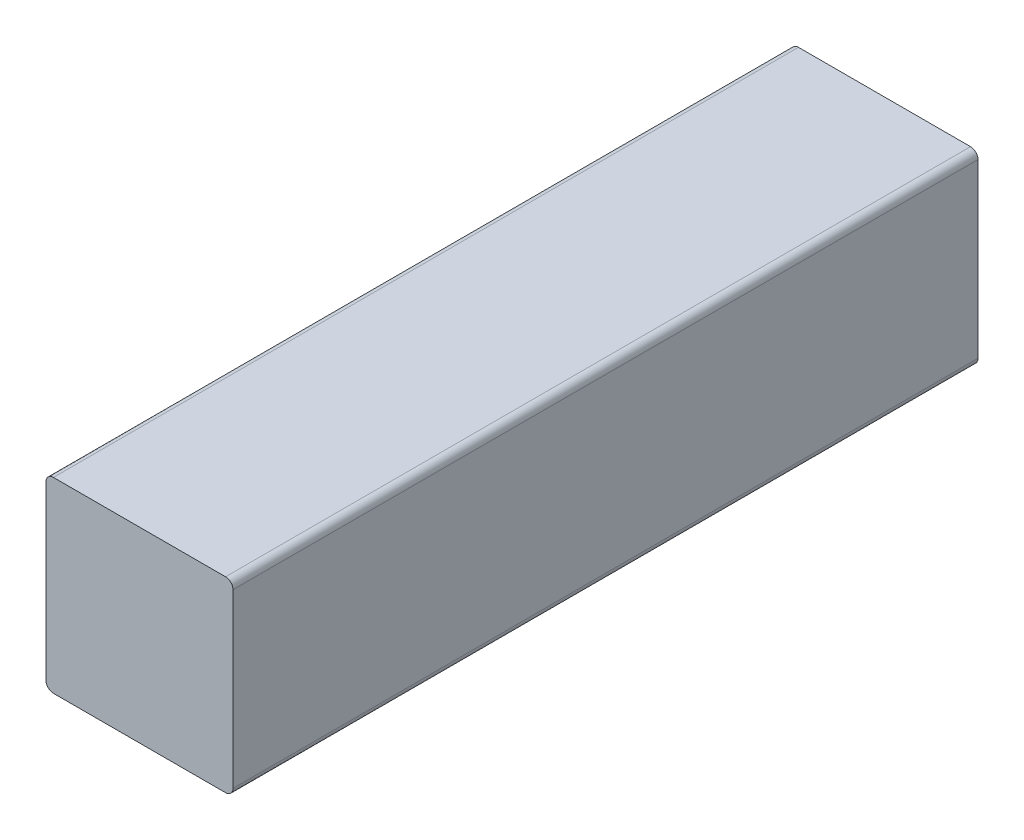
SolidWorks part; units mm, degrees
ref_plane "Front Plane" through (0, 0, 0) normal (0, 0, 1) x (1, 0, 0)
ref_plane "Top Plane" through (0, 0, 0) normal (0, 1, 0) x (1, 0, 0)
ref_plane "Right Plane" through (0, 0, 0) normal (1, 0, 0) x (0, 0, -1)
sketch "Sketch1" plane through (0, 0, 0) normal (0, 0, 1) x (1, 0, 0)
  line L0 (0.254, 0) -> (6.1214, 0)
  line L1 (6.3754, 0.254) -> (6.3754, 6.1214)
  line L2 (6.1214, 6.3754) -> (0.254, 6.3754)
  line L3 (0, 6.1214) -> (0, 0.254)
  arc A0 (0.254, 6.3754) -> (0, 6.1214) centre (0.254, 6.1214) ccw
  arc A1 (6.3754, 6.1214) -> (6.1214, 6.3754) centre (6.1214, 6.1214) ccw
  arc A2 (6.1214, 0) -> (6.3754, 0.254) centre (6.1214, 0.254) ccw
  arc A3 (0, 0.254) -> (0.254, 0) centre (0.254, 0.254) ccw
  point P13 (0, 0)
  dimension "D1" = 0.254
  dimension "D2" = 0.254
  dimension "D3" = 0.254
  dimension "D4" = 0.254
  dimension "D5" = 6.3754
  dimension "D6" = 6.3754
extrude "Boss-Extrude1" add sketch "Sketch1" along normal blind 25.4
